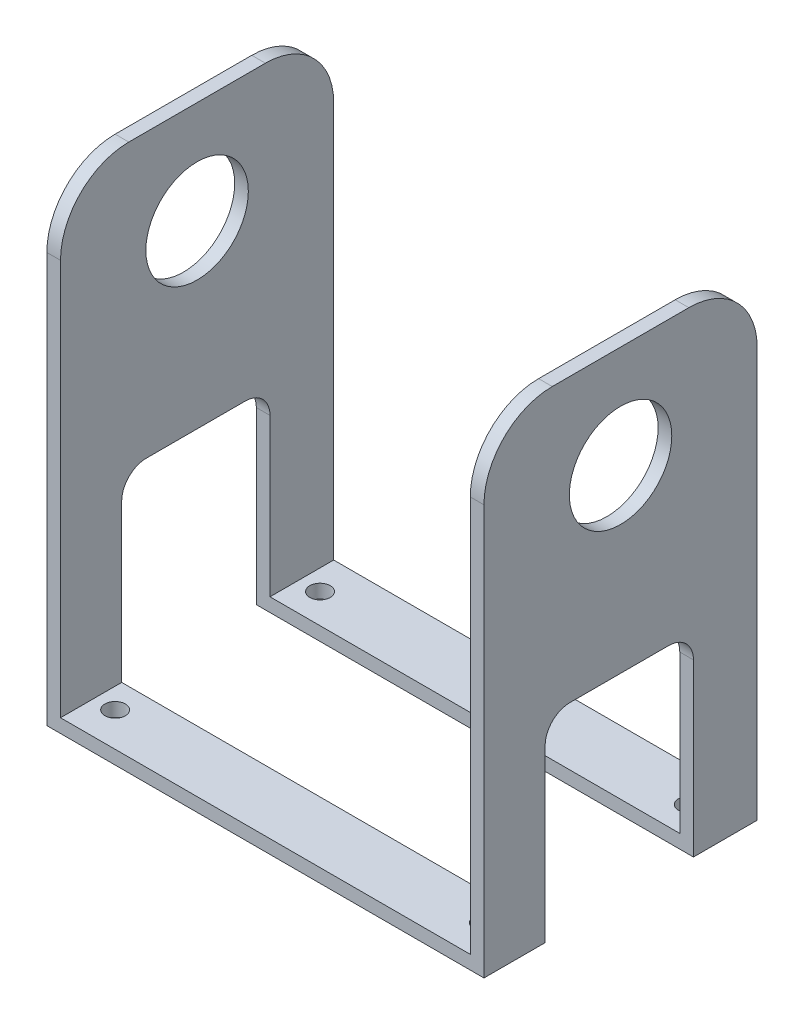
SolidWorks part; units mm, degrees
material "6061 Alloy"
ref_plane "Front Plane" through (0, 0, 0) normal (0, 0, 1) x (1, 0, 0)
ref_plane "Top Plane" through (0, 0, 0) normal (0, 1, 0) x (1, 0, 0)
ref_plane "Right Plane" through (0, 0, 0) normal (1, 0, 0) x (0, 0, -1)
sketch "Sketch1" plane through (0, 0, 0) normal (0, 0, 1) x (1, 0, 0)
  line L0 (-32, 0) -> (0, 0)
  line L1 (22, 0) -> (-22, 0) construction
  line L2 (0, 0) -> (0, 70)
  line L3 (0, -22) -> (0, 22) construction
  dimension "D1" = 70
  dimension "D2" = 32
extrude "Extrude-Thin1" add sketch "Sketch1" along normal blind 40 thin thin type one direction reverse wall 2
sketch "Sketch2" plane through (0, 0, 0) normal (1, 0, 0) x (0, 0, -1)
  line L0 (-31.0395, 0) -> (-31.0395, 25)
  line L1 (22, 0) -> (-22, 0) construction
  line L2 (-9.3277, 25) -> (-9.3277, 0)
  line L3 (-20, 70) -> (-20, 0) construction
  line L4 (-40, 70) -> (0, 70) construction
  line L5 (-31.0395, 0) -> (-9.3277, 0)
  line L6 (-27.4107, 28.6288) -> (-12.9564, 28.6288)
  arc A0 (-31.0395, 25) -> (-27.4107, 28.6288) centre (-27.4107, 25) cw
  circle A1 centre (-20, 55) radius 7.5
  arc A2 (-12.9564, 28.6288) -> (-9.3277, 25) centre (-12.9564, 25) cw
  dimension "D3" = 15
  dimension "D4" = 55
  dimension "D2" = 25
extrude "Cut-Extrude2" cut sketch "Sketch2" against normal blind 60 contours L3 A1 | A1 L3 | L2 L5 L0 A0 L6 A2
fillet "Fillet1" radius 10 2 edges at (-1, 70, 0) (-1, 70, 40)
mirror "Mirror1" about plane through (-32, 0, 40) normal (-1, 0, 0) of bodies 103 104
sketch "Sketch3" plane through (0, 0, 0) normal (0, -1, 0) x (1, 0, 0)
  line L5 (-64, 40) -> (0, 40) construction
  line L6 (-59, 35) -> (-5, 35) construction
  line L7 (-59, 35) -> (-59, 5) construction
  line L8 (-59, 5) -> (-5, 5) construction
  line L9 (-5, 35) -> (-5, 5) construction
  line L10 (-64, 40) -> (-64, 31.0395) construction
  line L11 (0, -22) -> (0, 22) construction
  line L12 (35.2, 0) -> (-35.2, 0) construction
  circle A0 centre (-59, 35) radius 1.5
  circle A1 centre (-5, 35) radius 1.5
  circle A2 centre (-5, 5) radius 1.5
  circle A3 centre (-59, 5) radius 1.5
  dimension "D1" = 5
  dimension "D2" = 5
  dimension "D3" = 5
  dimension "D4" = 5
  dimension "D5" = 3
extrude "Cut-Extrude4" cut sketch "Sketch3" against normal blind 20
